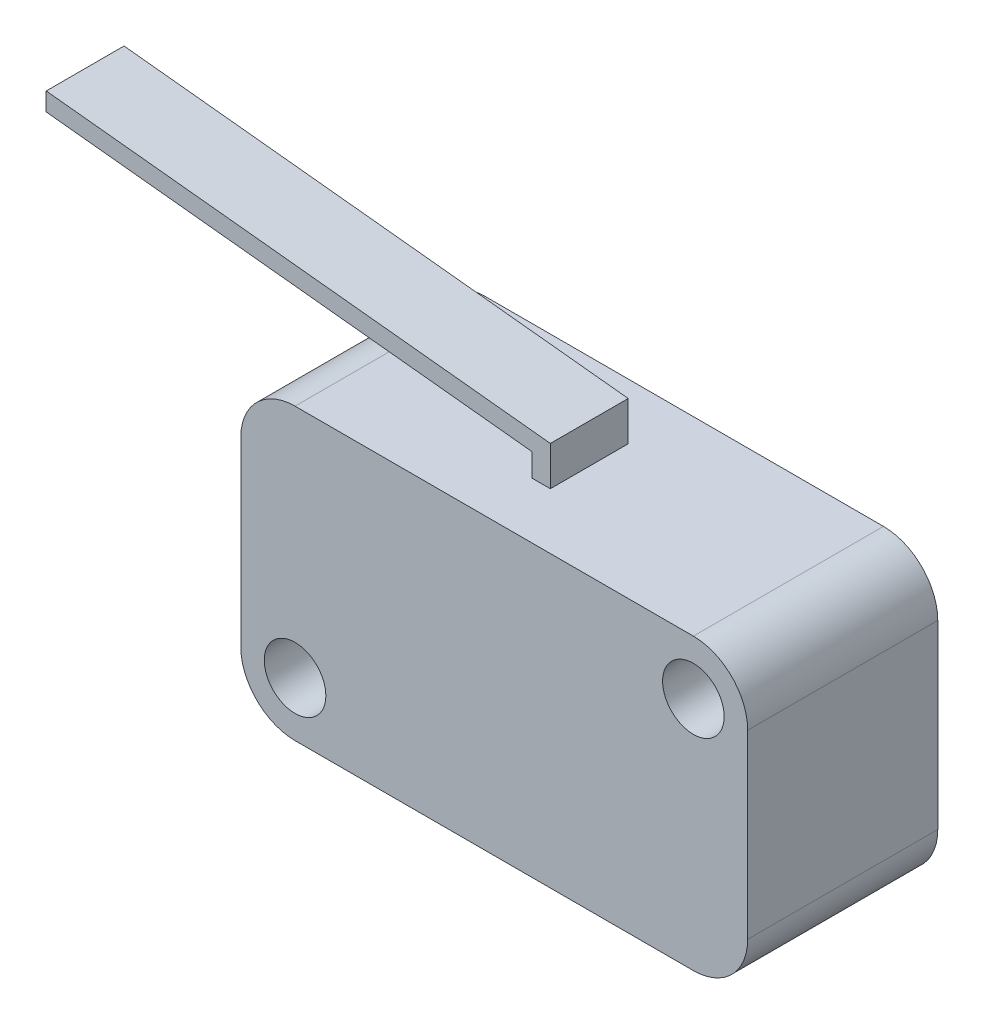
SolidWorks part; units mm, degrees
ref_plane "前视基准面" through (0, 0, 0) normal (0, 0, 1) x (1, 0, 0)
ref_plane "上视基准面" through (0, 0, 0) normal (0, 1, 0) x (1, 0, 0)
ref_plane "右视基准面" through (0, 0, 0) normal (1, 0, 0) x (0, 0, -1)
sketch "草图1" plane through (0, 0, 0) normal (0, 0, 1) x (1, 0, 0)
  line L1 (14, -8) -> (-14, -8)
  line L2 (14, -8) -> (14, 8)
  line L3 (14, 8) -> (-14, 8)
  line L4 (-14, -8) -> (-14, 8)
  line L5 (14, -8) -> (-14, 8) construction
  line L6 (14, 8) -> (-14, -8) construction
  point P0 (0, 0)
  dimension "D1" = 16
  dimension "D2" = 28
extrude "凸台-拉伸1" add sketch "草图1" along normal blind 10.5
sketch "草图2" plane through (0, 0, 10.5) normal (0, 0, 1) x (1, 0, 0)
  line L0 (14, 8) -> (-14, 8) construction
  line L1 (-14, -8) -> (14, -8) construction
  circle A0 centre (-11, -5) radius 1.7
  circle A1 centre (11, 5) radius 1.7
  dimension "D1" = 3.4
  dimension "D2" = 3.4
  dimension "D3" = 11
  dimension "D4" = 11
  dimension "D5" = 3
  dimension "D6" = 3
extrude "切除-拉伸1" cut sketch "草图2" against normal blind 10.5
fillet "圆角1" radius 3 4 edges at (-14, 8, 5.25) (14, 8, 5.25) (14, -8, 5.25) (-14, -8, 5.25)
sketch "草图3" plane through (0, 0, 0) normal (0, 0, 1) x (1, 0, 0)
  line L0 (0, 8) -> (0, 10.1671)
  line L1 (11, 8) -> (-11, 8) construction
  line L2 (0, 10.1671) -> (-27.8454, 13.1056)
  line L3 (-27.8454, 13.1056) -> (-27.8454, 12.1)
  line L4 (-27.8454, 12.1) -> (-1, 9.2671)
  line L5 (-1, 9.2671) -> (-1, 8)
  line L6 (-1, 8) -> (0, 8)
  dimension "D1" = 4.1
  dimension "D2" = 28
  dimension "D3" = 1
  dimension "D4" = 1
extrude "凸台-拉伸2" add sketch "草图3" along normal up to surface (10.5 mm away) up to face at (-9.3, -5, 10.5)
sketch "草图4" plane through (0, 0, 10.5) normal (0, 0, 1) x (1, 0, 0)
  line L1 (-27.8454, 13.1056) -> (0, 13.1056)
  line L2 (-27.8454, 13.1056) -> (-27.8454, 8)
  line L3 (-27.8454, 8) -> (0, 8)
  line L4 (0, 13.1056) -> (0, 8)
extrude "切除-拉伸2" cut sketch "草图4" against normal blind 3.1
sketch "草图5" plane through (0, 0, 0) normal (0, 0, -1) x (-1, 0, 0)
  line L1 (0, 8) -> (33.6435, 8)
  line L2 (0, 8) -> (0, 15.5932)
  line L3 (0, 15.5932) -> (33.6435, 15.5932)
  line L4 (33.6435, 8) -> (33.6435, 15.5932)
extrude "切除-拉伸3" cut sketch "草图5" against normal blind 3.1
